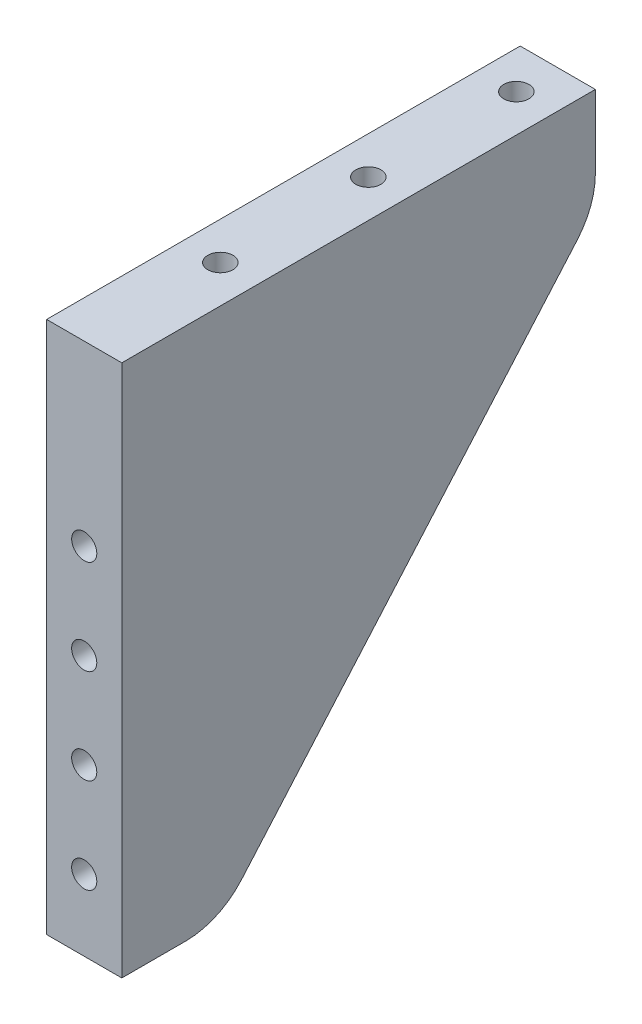
SolidWorks part; units mm, degrees
material "Low Carbon Steel"
ref_plane "Front Plane" through (0, 0, 0) normal (0, 0, 1) x (1, 0, 0)
ref_plane "Top Plane" through (0, 0, 0) normal (0, 1, 0) x (1, 0, 0)
ref_plane "Right Plane" through (0, 0, 0) normal (1, 0, 0) x (0, 0, -1)
sketch "Sketch1" plane through (0, 0, 0) normal (1, 0, 0) x (0, 0, -1)
  line L0 (0, 0) -> (26.7092, 0)
  line L1 (45.5744, 8.5955) -> (158.9651, 138.9949)
  line L2 (165.1, 155.3994) -> (165.1, 184.15)
  line L3 (165.1, 184.15) -> (0, 184.15)
  line L4 (0, 184.15) -> (0, 0)
  arc A0 (158.9651, 138.9949) -> (165.1, 155.3994) centre (140.1, 155.3994) ccw
  arc A1 (26.7092, 0) -> (45.5744, 8.5955) centre (26.7092, 25) ccw
  point P8 (165.1, 146.05)
  point P11 (38.1, 0)
  dimension "D5" = 25
  dimension "D1" = 38.1
  dimension "D2" = 38.1
  dimension "D3" = 184.15
  dimension "D4" = 165.1
extrude "Boss-Extrude1" add sketch "Sketch1" along normal mid plane 25.4
sketch "Sketch2" plane through (12.7, 0, 0) normal (1, 0, 0) x (0, 0, -1)
  line L0 (0, 184.15) -> (0, 0)
  line L1 (0, 0) -> (5.1, 0)
  line L2 (0, 0) -> (26.7092, 0) construction
  line L3 (5.1, 0) -> (5.1, 180)
  line L4 (5.1, 180) -> (165.1, 180)
  line L5 (165.1, 155.3994) -> (165.1, 184.15) construction
  line L6 (165.1, 180) -> (165.1, 184.15)
  line L7 (165.1, 184.15) -> (0, 184.15)
  dimension "D1" = 180
  dimension "D2" = 160
  dimension "D3" = 4.15
  dimension "D4" = 5.1
extrude "Cut-Extrude1" cut sketch "Sketch2" against normal blind 31.75 contours L4 L6 L7 L0 L1 L3
hole_wizard "M10 Tapped Hole1" positions "Sketch4" profile "Sketch3" tap size "M10" standard "Peddi DIN"
sketch "Sketch4" plane through (0, 180, 0) normal (0, 1, 0) x (1, 0, 0)
  line L0 (0, 5.1) -> (0, 51.1) construction
  line L1 (-12.7, 5.1) -> (12.7, 5.1) construction
  line L2 (0, 51.1) -> (0, 101.1) construction
  line L3 (0, 101.1) -> (0, 151.1) construction
  point P0 (0, 51.1)
  point P2 (0, 101.1)
  point P4 (0, 151.1)
  dimension "D1" = 46
  dimension "D2" = 50
sketch "Sketch3" plane through (0, 180, -51.1) normal (1, 0, 0) x (0, 0, 1)
  line L0 (0, 0) -> (0, 30.0537)
  line L1 (0, 30.0537) -> (4.25, 27.5)
  line L2 (4.25, 27.5) -> (4.25, 0)
  line L5 (4.25, 0) -> (0, 0)
  line L10 (0, 30.0537) -> (-4.25, 27.5) construction
  line L11 (0, -6.35) -> (0, 107.95) construction
  dimension "Tap Drill Dia." = 8.5
  dimension "Tap Drill Depth" = 27.5
  dimension "Drill Angle" = 118
cosmetic thread "Hole Thread1" parameters "D1"=24.99, "D2"=10
cosmetic thread "Hole Thread2" parameters "D1"=24.99, "D2"=10
cosmetic thread "Hole Thread3" parameters "D1"=24.99, "D2"=10
hole_wizard "M10 Tapped Hole2" positions "Sketch6" profile "Sketch5" tap size "M10" standard "Peddi DIN"
sketch "Sketch6" plane through (0, 0, -5.1) normal (0, 0, 1) x (1, 0, 0)
  line L0 (0, 120) -> (0, 88) construction
  line L1 (0, 88) -> (0, 56) construction
  line L2 (0, 56) -> (0, 24) construction
  line L4 (0, 120) -> (0, 180) construction
  line L5 (-12.7, 180) -> (12.7, 180) construction
  point P0 (0, 120)
  point P2 (0, 88)
  point P4 (0, 56)
  point P6 (0, 24)
  dimension "D1" = 60
  dimension "D2" = 32
sketch "Sketch5" plane through (0, 120, -5.1) normal (1, 0, 0) x (0, -1, 0)
  line L0 (0, 0) -> (0, 30.0537)
  line L1 (0, 30.0537) -> (4.25, 27.5)
  line L2 (4.25, 27.5) -> (4.25, 0)
  line L5 (4.25, 0) -> (0, 0)
  line L10 (0, 30.0537) -> (-4.25, 27.5) construction
  line L11 (0, -6.35) -> (0, 107.95) construction
  dimension "Tap Drill Dia." = 8.5
  dimension "Tap Drill Depth" = 27.5
  dimension "Drill Angle" = 118
cosmetic thread "Hole Thread4" parameters "D1"=24.99, "D2"=10
cosmetic thread "Hole Thread5" parameters "D1"=24.99, "D2"=10
cosmetic thread "Hole Thread6" parameters "D1"=24.99, "D2"=10
cosmetic thread "Hole Thread7" parameters "D1"=24.99, "D2"=10
other "Freeze***"
